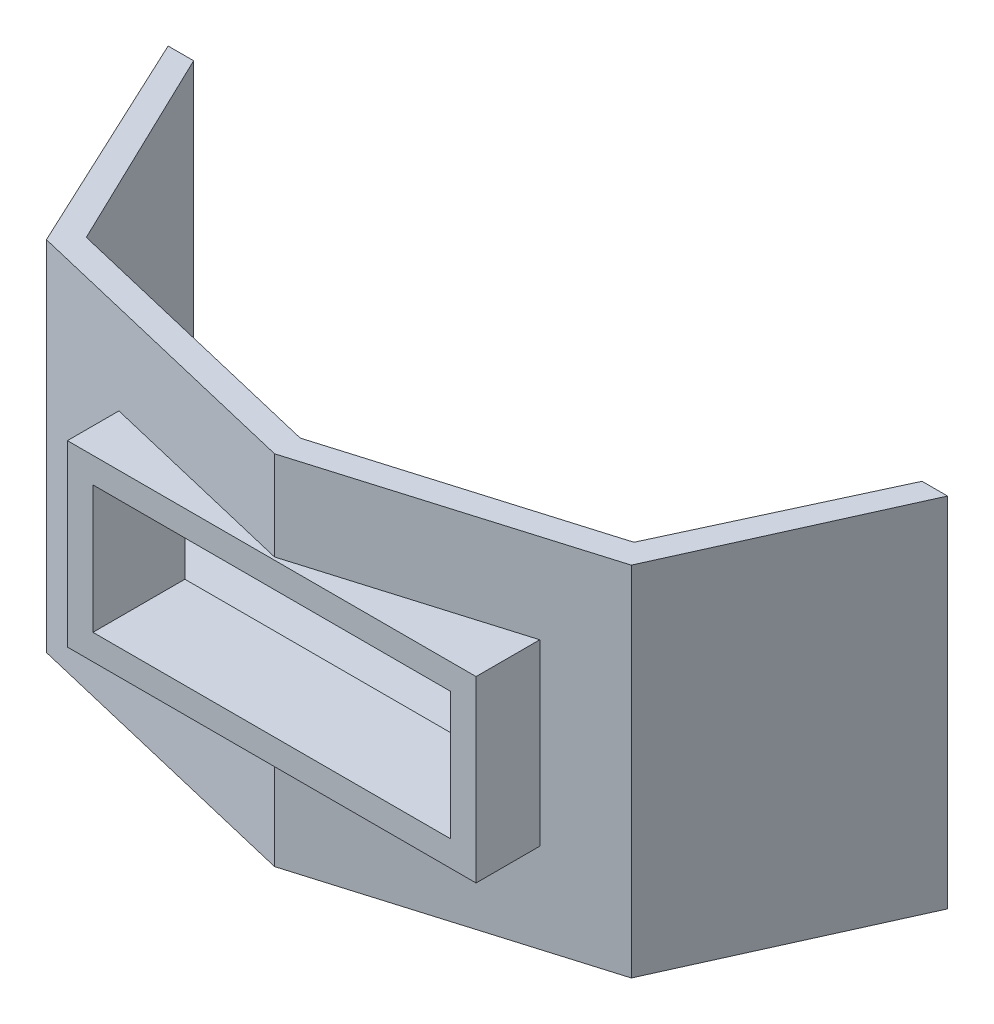
SolidWorks part; units mm, degrees
ref_plane "Front Plane" through (0, 0, 0) normal (0, 0, 1) x (1, 0, 0)
ref_plane "Top Plane" through (0, 0, 0) normal (0, 1, 0) x (1, 0, 0)
ref_plane "Right Plane" through (0, 0, 0) normal (1, 0, 0) x (0, 0, -1)
sketch "Sketch1" plane through (0, 0, 0) normal (0, 1, 0) x (1, 0, 0)
  line L15 (-55.374, -102.4826) -> (3.2527, -116.4495)
  line L16 (3.2527, -116.4495) -> (57.0602, -100.4088)
  line L19 (-55.374, -102.4826) -> (-76.3, -57.735)
  line L20 (57.0602, -100.4088) -> (76.3, -57.735)
  line L21 (-76.3, -57.735) -> (76.3, -57.735)
  line L23 (109.4621, -26.0776) -> (116.3881, 2.9946) [skipped]
  line L24 (-115.238, -7.3166) -> (-106.7, -35.9569) [skipped]
  line L25 (-103.4574, 51.2826) -> (-110.3834, 22.2104) [skipped]
  line L26 (96.1407, 63.9554) -> (74.4264, 84.4896) [skipped]
  line L27 (115.238, 7.3166) -> (98.162, 64.5972) [skipped]
  line L28 (26.0776, 109.4621) -> (-2.9946, 116.3881) [skipped]
  line L29 (-7.3166, 115.238) -> (-35.9569, 106.7) [skipped]
  line L30 (-63.9554, 96.1407) -> (-84.4896, 74.4264) [skipped]
  line L31 (-77.3149, -81.7581) -> (-55.6006, -102.2923) [skipped]
  line L32 (81.7581, -77.3149) -> (102.2923, -55.6006) [skipped]
  arc A1 (-59.5591, -93.5334) -> (60.4055, -92.9891) centre (0, 0) ccw construction
  dimension "D3" = 76.3
  dimension "D4" = 76.3
extrude "Boss-Extrude1" add sketch "Sketch1" along normal blind 70
sketch "Sketch4" plane through (0, 70, 0) normal (0, 1, 0) x (1, 0, 0)
  line L9 (-51.8673, -98.1781) -> (3.1082, -111.2752)
  line L10 (3.1082, -111.2752) -> (53.4415, -96.2702)
  line L13 (-55.374, -102.4826) -> (3.2527, -116.4495) construction
  line L14 (-51.8673, -98.1781) -> (-71.3, -57.735)
  line L16 (76.3, -57.735) -> (-76.3, -57.735) construction
  line L17 (53.4415, -96.2702) -> (71.3, -57.735)
  line L18 (-71.3, -57.735) -> (71.3, -57.735)
  line L19 (-76.3, -57.735) -> (-55.374, -102.4826) construction
  line L20 (-73.8794, -78.1253) -> (-53.1386, -97.7389) [skipped]
  line L21 (61.2536, -91.7207) -> (100.4809, -50.239) [skipped]
  line L22 (104.5982, -24.9188) -> (111.2137, 2.8501) [skipped]
  line L23 (-78.1253, 73.8794) -> (-97.7389, 53.1386) [skipped]
  line L24 (-110.0593, -7.1868) -> (-93.7487, -61.8995) [skipped]
  line L25 (-104.5982, 24.9188) -> (-111.2137, -2.8501) [skipped]
  line L26 (24.9188, 104.5982) -> (-2.8501, 111.2137) [skipped]
  line L27 (91.7207, 61.2536) -> (70.9799, 80.8672) [skipped]
  line L28 (103.0441, 30.7187) -> (94.8888, 58.0751) [skipped]
  line L29 (-30.7187, 103.0441) -> (-58.0751, 94.8888) [skipped]
  line L30 (57.0602, -100.4088) -> (76.3, -57.735) construction
  dimension "D1" = 5
  dimension "D2" = 5
  dimension "D3" = 5
  dimension "D4" = 5
  dimension "D5" = 5
extrude "Cut-Extrude1" cut sketch "Sketch4" against normal blind 65
ref_plane "Plane1" through (0, 0, 117) normal (0, 0, 1) x (1, 0, 0)
sketch "Sketch5" plane through (0, 0, 117) normal (0, 0, 1) x (1, 0, 0)
  line L0 (3.2527, 70) -> (3.2527, 0) construction
  line L1 (-36.7473, 52.5) -> (43.2527, 52.5)
  line L2 (-36.7473, 52.5) -> (-36.7473, 17.5)
  line L3 (-36.7473, 17.5) -> (43.2527, 17.5)
  line L4 (43.2527, 52.5) -> (43.2527, 17.5)
  line L5 (-36.7473, 52.5) -> (43.2527, 17.5) construction
  line L6 (-36.7473, 17.5) -> (43.2527, 52.5) construction
  point P0 (3.2527, 35)
  dimension "D1" = 80
  dimension "D2" = 35
extrude "Boss-Extrude2" add sketch "Sketch5" against normal blind 18
sketch "Sketch6" plane through (0, 0, 117) normal (0, 0, 1) x (1, 0, 0)
  line L0 (-36.7473, 17.5) -> (43.2527, 17.5) construction
  line L1 (-31.7473, 47.5) -> (38.2527, 47.5)
  line L2 (-31.7473, 47.5) -> (-31.7473, 22.5)
  line L3 (-31.7473, 22.5) -> (38.2527, 22.5)
  line L4 (38.2527, 47.5) -> (38.2527, 22.5)
  line L5 (-31.7473, 47.5) -> (38.2527, 22.5) construction
  line L6 (-31.7473, 22.5) -> (38.2527, 47.5) construction
  line L8 (-36.7473, 17.5) -> (-36.7473, 52.5) construction
  point P0 (3.2527, 35)
  point P7 (0, 0)
  dimension "D1" = 70
  dimension "D2" = 25
  dimension "D3" = 17.5
  dimension "D4" = 40
extrude "Cut-Extrude2" cut sketch "Sketch6" against normal blind 18
